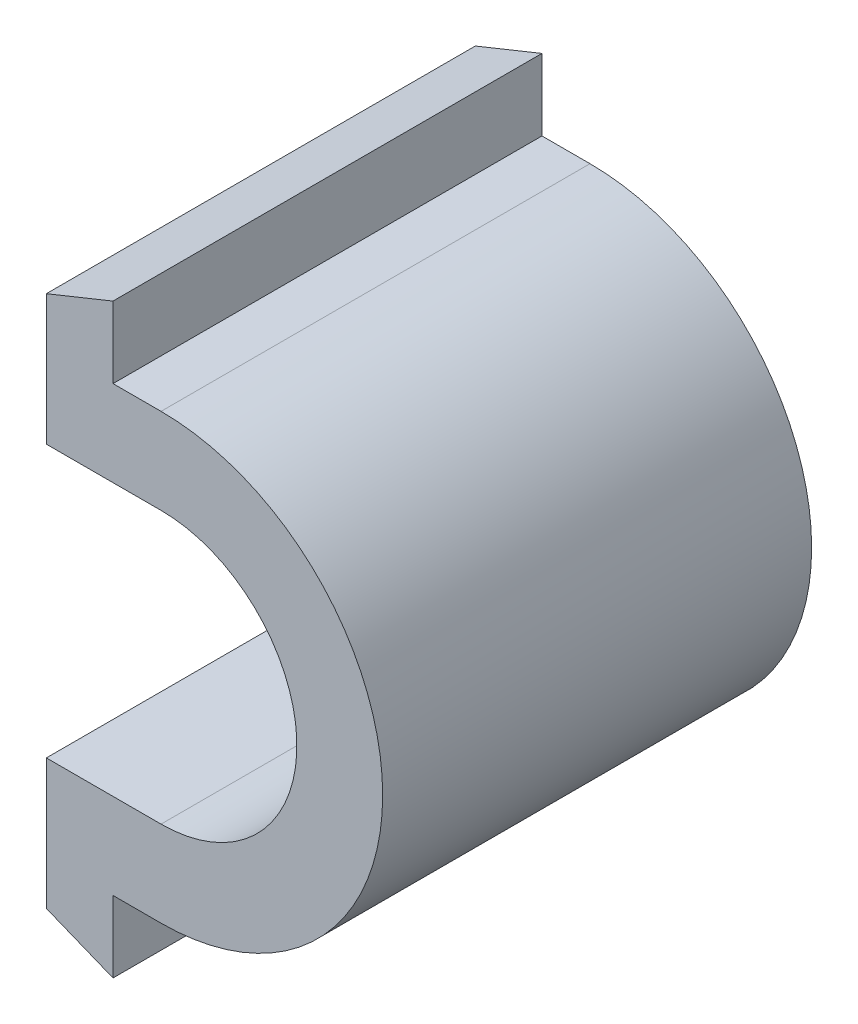
SolidWorks part; units mm, degrees
ref_plane "Front" through (0, 0, 0) normal (0, 0, 1) x (1, 0, 0)
ref_plane "Top" through (0, 0, 0) normal (0, 1, 0) x (1, 0, 0)
ref_plane "Right" through (0, 0, 0) normal (1, 0, 0) x (0, 0, -1)
sketch "Skizze1" plane through (0, 0, 0) normal (0, 0, 1) x (1, 0, 0)
  line L0 (0, 0) -> (5.6951, 0) construction
  line L1 (0.9323, 3.1) -> (1.6042, 3.1)
  line L2 (0, 3.3565) -> (0, 1.9)
  line L3 (0, 1.9) -> (1.6042, 1.9)
  line L4 (0, -1.9) -> (1.6042, -1.9)
  line L5 (0, -3.3565) -> (0, -1.9)
  line L6 (0.9323, -3.1) -> (1.6042, -3.1)
  line L7 (0.9323, 3.1) -> (0.9323, 4.1)
  line L8 (0.9323, 4.1) -> (0, 3.7234)
  line L9 (0, 3.7234) -> (0, 3.3565)
  line L10 (0, -3.7234) -> (0, -3.3565)
  line L11 (0.9323, -4.1) -> (0, -3.7234)
  line L12 (0.9323, -3.1) -> (0.9323, -4.1)
  arc A0 (1.6042, 3.1) -> (1.6042, -3.1) centre (1.6042, 0) cw
  arc A1 (1.6042, 1.9) -> (1.6042, -1.9) centre (1.6042, 0) cw
  point P12 (0, 3.7234)
  point P19 (0.8795, 3.1)
  point P20 (0.9323, 4.1)
  dimension "D1" = 6.2
  dimension "D2" = 1.2
  dimension "D4" = 1
extrude "Aufsatz-Linear austragen1" add sketch "Skizze1" along normal blind 6
